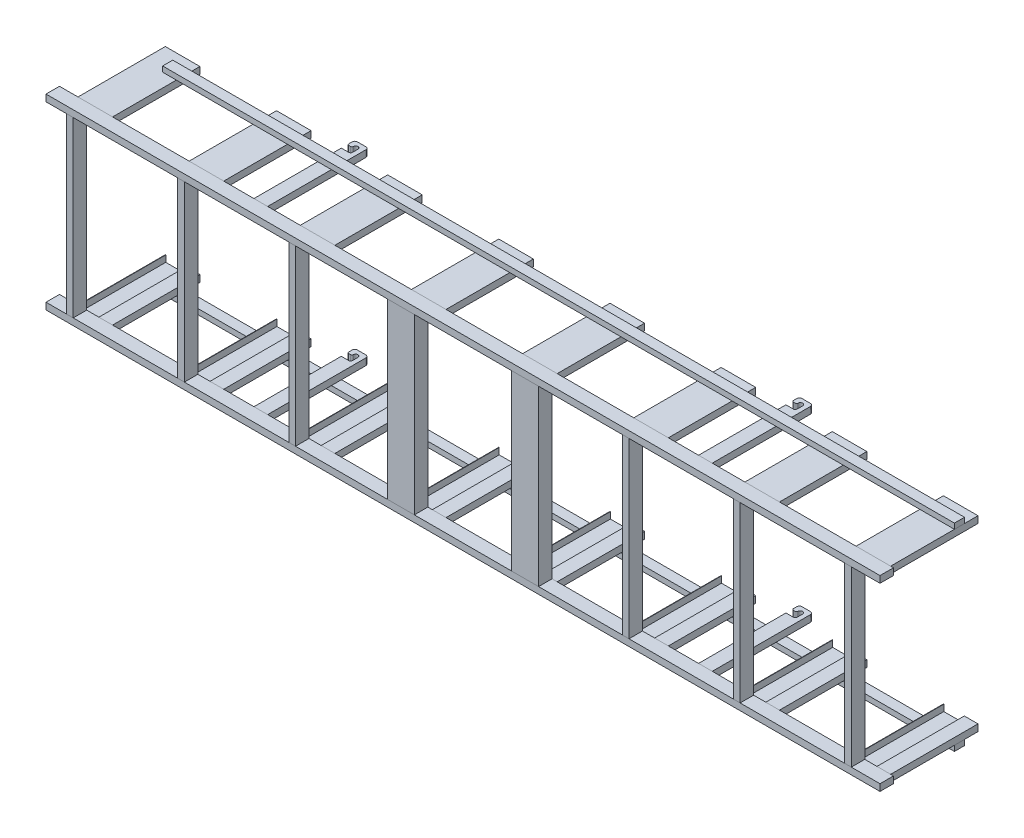
SolidWorks part; units mm, degrees
ref_plane "Front Plane" through (0, 0, 0) normal (0, 0, 1) x (1, 0, 0)
ref_plane "Top Plane" through (0, 0, 0) normal (0, 1, 0) x (1, 0, 0)
ref_plane "Right Plane" through (0, 0, 0) normal (1, 0, 0) x (0, 0, -1)
sketch "Sketch1" plane through (0, 0, 0) normal (0, 0, 1) x (1, 0, 0)
  line L0 (0, 1388) -> (6190, 1388)
  line L1 (0, 50) -> (6190, 50)
  line L2 (0, 50) -> (0, 0)
  line L3 (0, 0) -> (6190, 0)
  line L4 (6190, 50) -> (6190, 0)
  line L5 (0, 1388) -> (0, 1338)
  line L6 (0, 1338) -> (6190, 1338)
  line L7 (6190, 1388) -> (6190, 1338)
  dimension "D1" = 1288
  dimension "D2" = 50
extrude "Boss-Extrude1" add sketch "Sketch1" along normal blind 100
sketch "Sketch2" plane through (0, 0, 0) normal (0, -1, 0) x (1, 0, 0)
  line L0 (0, 100) -> (6190, 100) construction
  line L1 (2534, 100) -> (2734, 100)
  line L2 (2534, 100) -> (2534, 0)
  line L3 (2534, 0) -> (2734, 0)
  line L4 (2734, 100) -> (2734, 0)
  line L5 (0, 0) -> (6190, 0) construction
  line L6 (0, 100) -> (0, 0) construction
  line L8 (3456, 100) -> (3656, 100)
  line L9 (3456, 100) -> (3456, 0)
  line L10 (3456, 0) -> (3656, 0)
  line L11 (3656, 100) -> (3656, 0)
  point P8 (0, 50)
  dimension "D1" = 200
  dimension "D2" = 2534
  dimension "D3" = 2534
  dimension "D4" = 200
extrude "Boss-Extrude2" add sketch "Sketch2" against normal up to surface (1388 mm away) separate body up to face at (3095, 1388, 50)
sketch "Sketch3" plane through (0, 1388, 0) normal (0, 1, 0) x (1, 0, 0)
  line L2 (0, -100) -> (0, 0) construction
  line L3 (6190, -100) -> (6190, 0) construction
  line L12 (2541, -7) -> (2727, -7)
  line L13 (2727, -7) -> (2727, -93)
  line L14 (2541, -93) -> (2727, -93)
  line L15 (2541, -7) -> (2541, -93)
  line L16 (3463, -7) -> (3649, -7)
  line L17 (3649, -7) -> (3649, -93)
  line L18 (3463, -93) -> (3649, -93)
  line L19 (3463, -7) -> (3463, -93)
  point P2 (6190, -50)
  dimension "D1" = 186
  dimension "D2" = 186
  dimension "D3" = 2541
  dimension "D4" = 2541
extrude "Cut-Extrude1" [suppressed] cut sketch "Sketch3" against normal through all
sketch "Sketch4" plane through (0, 50, 0) normal (0, 1, 0) x (1, 0, 0)
  line L0 (6190, 0) -> (0, 0) construction
  line L1 (152, 0) -> (202, 0)
  line L2 (152, 0) -> (152, -100)
  line L3 (152, -100) -> (202, -100)
  line L4 (202, 0) -> (202, -100)
  line L5 (6190, -100) -> (0, -100) construction
  line L6 (0, -100) -> (0, 0) construction
  line L7 (977, 0) -> (977, -100)
  line L8 (977, 0) -> (1027, 0)
  line L9 (1027, 0) -> (1027, -100)
  line L10 (977, -100) -> (1027, -100)
  line L11 (1802, 0) -> (1802, -100)
  line L12 (1802, 0) -> (1852, 0)
  line L13 (1852, 0) -> (1852, -100)
  line L14 (1802, -100) -> (1852, -100)
  line L15 (2627, 0) -> (2627, -100) construction
  line L16 (2627, 0) -> (2677, 0) construction
  line L17 (2677, 0) -> (2677, -100) construction
  line L18 (2627, -100) -> (2677, -100) construction
  line L19 (3452, 0) -> (3452, -100) construction
  line L20 (3452, 0) -> (3502, 0) construction
  line L21 (3502, 0) -> (3502, -100) construction
  line L22 (3452, -100) -> (3502, -100) construction
  line L23 (4277, 0) -> (4277, -100)
  line L24 (4277, 0) -> (4327, 0)
  line L25 (4327, 0) -> (4327, -100)
  line L26 (4277, -100) -> (4327, -100)
  line L27 (5102, 0) -> (5102, -100)
  line L28 (5102, 0) -> (5152, 0)
  line L29 (5152, 0) -> (5152, -100)
  line L30 (5102, -100) -> (5152, -100)
  line L31 (5927, 0) -> (5927, -100)
  line L32 (5927, 0) -> (5977, 0)
  line L33 (5977, 0) -> (5977, -100)
  line L34 (5927, -100) -> (5977, -100)
  dimension "D1" = 152
  dimension "D2" = 50
  dimension "D3" = 8
extrude "Boss-Extrude3" add sketch "Sketch4" along normal up to next separate body
sketch "Sketch5" plane through (0, 0, 0) normal (0, 0, 1) x (1, 0, 0)
  line L0 (137.4, 1388) -> (137.4, 1338)
  line L1 (140.4, 1385.8) -> (140.4, 1338)
  line L2 (292.4, 1385.8) -> (140.4, 1385.8)
  line L3 (394, 1388) -> (394, 1338)
  line L4 (137.4, 1388) -> (394, 1388)
  line L5 (394, 1338) -> (292.4, 1338)
  line L6 (140.4, 1338) -> (137.4, 1338)
  line L7 (292.4, 1385.8) -> (292.4, 1338)
  line L8 (152, 1338) -> (137.4, 1338) construction
  line L9 (0, 1338) -> (2534, 1338) construction
  line L10 (962.4, 1388) -> (962.4, 1338)
  line L11 (965.4, 1385.8) -> (965.4, 1338)
  line L12 (1117.4, 1385.8) -> (965.4, 1385.8)
  line L13 (1219, 1388) -> (1219, 1338)
  line L14 (962.4, 1388) -> (1219, 1388)
  line L15 (1219, 1338) -> (1117.4, 1338)
  line L16 (965.4, 1338) -> (962.4, 1338)
  line L17 (1117.4, 1385.8) -> (1117.4, 1338)
  line L18 (977, 1338) -> (962.4, 1338) construction
  line L19 (1787.4, 1388) -> (1787.4, 1338)
  line L20 (1790.4, 1385.8) -> (1790.4, 1338)
  line L21 (1942.4, 1385.8) -> (1790.4, 1385.8)
  line L22 (2044, 1388) -> (2044, 1338)
  line L23 (1787.4, 1388) -> (2044, 1388)
  line L24 (2044, 1338) -> (1942.4, 1338)
  line L25 (1790.4, 1338) -> (1787.4, 1338)
  line L26 (1942.4, 1385.8) -> (1942.4, 1338)
  line L27 (1802, 1338) -> (1787.4, 1338) construction
  line L28 (2612.4, 1388) -> (2612.4, 1338)
  line L29 (2615.4, 1385.8) -> (2615.4, 1338)
  line L30 (2767.4, 1385.8) -> (2615.4, 1385.8)
  line L31 (2869, 1388) -> (2869, 1338)
  line L32 (2612.4, 1388) -> (2869, 1388)
  line L33 (2869, 1338) -> (2767.4, 1338)
  line L34 (2615.4, 1338) -> (2612.4, 1338)
  line L35 (2767.4, 1385.8) -> (2767.4, 1338)
  line L36 (2627, 1338) -> (2612.4, 1338) construction
  line L37 (3437.4, 1388) -> (3437.4, 1338)
  line L38 (3440.4, 1385.8) -> (3440.4, 1338)
  line L39 (3592.4, 1385.8) -> (3440.4, 1385.8)
  line L40 (3694, 1388) -> (3694, 1338)
  line L41 (3437.4, 1388) -> (3694, 1388)
  line L42 (3694, 1338) -> (3592.4, 1338)
  line L43 (3440.4, 1338) -> (3437.4, 1338)
  line L44 (3592.4, 1385.8) -> (3592.4, 1338)
  line L45 (3452, 1338) -> (3437.4, 1338) construction
  line L46 (4262.4, 1388) -> (4262.4, 1338)
  line L47 (4265.4, 1385.8) -> (4265.4, 1338)
  line L48 (4417.4, 1385.8) -> (4265.4, 1385.8)
  line L49 (4519, 1388) -> (4519, 1338)
  line L50 (4262.4, 1388) -> (4519, 1388)
  line L51 (4519, 1338) -> (4417.4, 1338)
  line L52 (4265.4, 1338) -> (4262.4, 1338)
  line L53 (4417.4, 1385.8) -> (4417.4, 1338)
  line L54 (4277, 1338) -> (4262.4, 1338) construction
  line L55 (5087.4, 1388) -> (5087.4, 1338)
  line L56 (5090.4, 1385.8) -> (5090.4, 1338)
  line L57 (5242.4, 1385.8) -> (5090.4, 1385.8)
  line L58 (5344, 1388) -> (5344, 1338)
  line L59 (5087.4, 1388) -> (5344, 1388)
  line L60 (5344, 1338) -> (5242.4, 1338)
  line L61 (5090.4, 1338) -> (5087.4, 1338)
  line L62 (5242.4, 1385.8) -> (5242.4, 1338)
  line L63 (5102, 1338) -> (5087.4, 1338) construction
  line L64 (5912.4, 1388) -> (5912.4, 1338)
  line L65 (5915.4, 1385.8) -> (5915.4, 1338)
  line L66 (6067.4, 1385.8) -> (5915.4, 1385.8)
  line L67 (6169, 1388) -> (6169, 1338)
  line L68 (5912.4, 1388) -> (6169, 1388)
  line L69 (6169, 1338) -> (6067.4, 1338)
  line L70 (5915.4, 1338) -> (5912.4, 1338)
  line L71 (6067.4, 1385.8) -> (6067.4, 1338)
  line L72 (5927, 1338) -> (5912.4, 1338) construction
  line L73 (152, 694) -> (5977, 694) construction
  line L74 (152, 1338) -> (152, 50) construction
  line L75 (5977, 1338) -> (5977, 50) construction
  line L76 (5927, 50) -> (5912.4, 50) construction
  line L77 (5102, 50) -> (5087.4, 50) construction
  line L78 (4277, 50) -> (4262.4, 50) construction
  line L79 (3452, 50) -> (3437.4, 50) construction
  line L80 (2627, 50) -> (2612.4, 50) construction
  line L81 (1802, 50) -> (1787.4, 50) construction
  line L82 (977, 50) -> (962.4, 50) construction
  line L83 (152, 50) -> (137.4, 50) construction
  line L84 (6067.4, 2.2) -> (6067.4, 50)
  line L85 (5915.4, 50) -> (5912.4, 50)
  line L86 (6169, 50) -> (6067.4, 50)
  line L87 (5912.4, 0) -> (6169, 0)
  line L88 (6169, 0) -> (6169, 50)
  line L89 (6067.4, 2.2) -> (5915.4, 2.2)
  line L90 (5915.4, 2.2) -> (5915.4, 50)
  line L91 (5912.4, 0) -> (5912.4, 50)
  line L92 (5242.4, 2.2) -> (5242.4, 50)
  line L93 (5090.4, 50) -> (5087.4, 50)
  line L94 (5344, 50) -> (5242.4, 50)
  line L95 (5087.4, 0) -> (5344, 0)
  line L96 (5344, 0) -> (5344, 50)
  line L97 (5242.4, 2.2) -> (5090.4, 2.2)
  line L98 (5090.4, 2.2) -> (5090.4, 50)
  line L99 (5087.4, 0) -> (5087.4, 50)
  line L100 (4417.4, 2.2) -> (4417.4, 50)
  line L101 (4265.4, 50) -> (4262.4, 50)
  line L102 (4519, 50) -> (4417.4, 50)
  line L103 (4262.4, 0) -> (4519, 0)
  line L104 (4519, 0) -> (4519, 50)
  line L105 (4417.4, 2.2) -> (4265.4, 2.2)
  line L106 (4265.4, 2.2) -> (4265.4, 50)
  line L107 (4262.4, 0) -> (4262.4, 50)
  line L108 (3592.4, 2.2) -> (3592.4, 50)
  line L109 (3440.4, 50) -> (3437.4, 50)
  line L110 (3694, 50) -> (3592.4, 50)
  line L111 (3437.4, 0) -> (3694, 0)
  line L112 (3694, 0) -> (3694, 50)
  line L113 (3592.4, 2.2) -> (3440.4, 2.2)
  line L114 (3440.4, 2.2) -> (3440.4, 50)
  line L115 (3437.4, 0) -> (3437.4, 50)
  line L116 (2767.4, 2.2) -> (2767.4, 50)
  line L117 (2615.4, 50) -> (2612.4, 50)
  line L118 (2869, 50) -> (2767.4, 50)
  line L119 (2612.4, 0) -> (2869, 0)
  line L120 (2869, 0) -> (2869, 50)
  line L121 (2767.4, 2.2) -> (2615.4, 2.2)
  line L122 (2615.4, 2.2) -> (2615.4, 50)
  line L123 (2612.4, 0) -> (2612.4, 50)
  line L124 (1942.4, 2.2) -> (1942.4, 50)
  line L125 (1790.4, 50) -> (1787.4, 50)
  line L126 (2044, 50) -> (1942.4, 50)
  line L127 (1787.4, 0) -> (2044, 0)
  line L128 (2044, 0) -> (2044, 50)
  line L129 (1942.4, 2.2) -> (1790.4, 2.2)
  line L130 (1790.4, 2.2) -> (1790.4, 50)
  line L131 (1787.4, 0) -> (1787.4, 50)
  line L132 (1117.4, 2.2) -> (1117.4, 50)
  line L133 (965.4, 50) -> (962.4, 50)
  line L134 (1219, 50) -> (1117.4, 50)
  line L135 (962.4, 0) -> (1219, 0)
  line L136 (1219, 0) -> (1219, 50)
  line L137 (1117.4, 2.2) -> (965.4, 2.2)
  line L138 (965.4, 2.2) -> (965.4, 50)
  line L139 (962.4, 0) -> (962.4, 50)
  line L140 (292.4, 2.2) -> (292.4, 50)
  line L141 (140.4, 50) -> (137.4, 50)
  line L142 (394, 50) -> (292.4, 50)
  line L143 (137.4, 0) -> (394, 0)
  line L144 (394, 0) -> (394, 50)
  line L145 (292.4, 2.2) -> (140.4, 2.2)
  line L146 (140.4, 2.2) -> (140.4, 50)
  line L147 (137.4, 0) -> (137.4, 50)
  dimension "D1" = 50
  dimension "D2" = 50
  dimension "D3" = 8
extrude "Boss-Extrude4" add sketch "Sketch5" against normal blind 648.4 separate body
sketch "Sketch8" plane through (0, 50, 0) normal (0, 1, 0) x (1, 0, 0)
  line L0 (1443.4, 648.4) -> (1497.5, 648.4)
  line L1 (1453.4, 693.4) -> (1467.5, 693.4)
  line L2 (1443.4, 728.4) -> (1443.4, 703.4)
  line L3 (1512.5, 703.4) -> (1512.5, 663.4)
  line L4 (1545, 0) -> (1443.4, 0)
  line L5 (1443.4, 0) -> (1443.4, 648.4)
  line L6 (1545, 0) -> (1545, 728.4)
  line L7 (1463.4, 748.4) -> (1525, 748.4)
  line L8 (0, 0) -> (1443.4, 0) construction
  line L9 (6190, 0) -> (4845, 0) construction
  line L10 (4845, 0) -> (4743.4, 0)
  line L11 (4812.5, 703.4) -> (4812.5, 663.4)
  line L12 (4743.4, 728.4) -> (4743.4, 703.4)
  line L13 (4753.4, 693.4) -> (4767.5, 693.4)
  line L14 (4743.4, 0) -> (4743.4, 648.4)
  line L15 (4845, 0) -> (4845, 728.4)
  line L16 (4743.4, 648.4) -> (4797.5, 648.4)
  line L17 (4763.4, 748.4) -> (4825, 748.4)
  arc A0 (1497.5, 648.4) -> (1512.5, 663.4) centre (1497.5, 663.4) ccw
  arc A1 (1443.4, 703.4) -> (1453.4, 693.4) centre (1453.4, 703.4) ccw
  arc A2 (1463.4, 748.4) -> (1443.4, 728.4) centre (1463.4, 728.4) ccw
  arc A3 (1545, 728.4) -> (1525, 748.4) centre (1525, 728.4) ccw
  arc A4 (1512.5, 703.4) -> (1477.5, 703.4) centre (1495, 703.4) ccw
  arc A5 (1467.5, 693.4) -> (1477.5, 703.4) centre (1467.5, 703.4) ccw
  arc A6 (4845, 728.4) -> (4825, 748.4) centre (4825, 728.4) ccw
  arc A7 (4763.4, 748.4) -> (4743.4, 728.4) centre (4763.4, 728.4) ccw
  arc A8 (4767.5, 693.4) -> (4777.5, 703.4) centre (4767.5, 703.4) ccw
  arc A9 (4743.4, 703.4) -> (4753.4, 693.4) centre (4753.4, 703.4) ccw
  arc A10 (4812.5, 703.4) -> (4777.5, 703.4) centre (4795, 703.4) ccw
  arc A11 (4797.5, 648.4) -> (4812.5, 663.4) centre (4797.5, 663.4) ccw
extrude "Boss-Extrude5" add sketch "Sketch8" against normal blind 50 separate body
sketch "Sketch9" plane through (0, 1388, 0) normal (0, 1, 0) x (1, 0, 0)
  line L0 (1443.4, 648.4) -> (1497.5, 648.4)
  line L1 (1453.4, 693.4) -> (1467.5, 693.4)
  line L2 (1443.4, 728.4) -> (1443.4, 703.4)
  line L3 (1512.5, 703.4) -> (1512.5, 663.4)
  line L4 (1545, 0) -> (1443.4, 0)
  line L5 (1443.4, 0) -> (1443.4, 648.4)
  line L6 (1545, 0) -> (1545, 728.4)
  line L7 (1463.4, 748.4) -> (1525, 748.4)
  line L8 (0, 0) -> (1443.4, 0) construction
  line L9 (6190, 0) -> (4845, 0) construction
  line L10 (4845, 0) -> (4743.4, 0)
  line L11 (4812.5, 703.4) -> (4812.5, 663.4)
  line L12 (4743.4, 728.4) -> (4743.4, 703.4)
  line L13 (4753.4, 693.4) -> (4767.5, 693.4)
  line L14 (4743.4, 0) -> (4743.4, 648.4)
  line L15 (4845, 0) -> (4845, 728.4)
  line L16 (4743.4, 648.4) -> (4797.5, 648.4)
  line L17 (4763.4, 748.4) -> (4825, 748.4)
  arc A0 (1497.5, 648.4) -> (1512.5, 663.4) centre (1497.5, 663.4) ccw
  arc A1 (1443.4, 703.4) -> (1453.4, 693.4) centre (1453.4, 703.4) ccw
  arc A2 (1463.4, 748.4) -> (1443.4, 728.4) centre (1463.4, 728.4) ccw
  arc A3 (1545, 728.4) -> (1525, 748.4) centre (1525, 728.4) ccw
  arc A4 (1512.5, 703.4) -> (1477.5, 703.4) centre (1495, 703.4) ccw
  arc A5 (1467.5, 693.4) -> (1477.5, 703.4) centre (1467.5, 703.4) ccw
  arc A6 (4845, 728.4) -> (4825, 748.4) centre (4825, 728.4) ccw
  arc A7 (4763.4, 748.4) -> (4743.4, 728.4) centre (4763.4, 728.4) ccw
  arc A8 (4767.5, 693.4) -> (4777.5, 703.4) centre (4767.5, 703.4) ccw
  arc A9 (4743.4, 703.4) -> (4753.4, 693.4) centre (4753.4, 703.4) ccw
  arc A10 (4812.5, 703.4) -> (4777.5, 703.4) centre (4795, 703.4) ccw
  arc A11 (4797.5, 648.4) -> (4812.5, 663.4) centre (4797.5, 663.4) ccw
extrude "Boss-Extrude6" add sketch "Sketch9" against normal blind 50 separate body
sketch "Sketch10" plane through (6169, 0, 0) normal (1, 0, 0) x (0, 0, -1)
  line L0 (648.4, 0) -> (0, 0) construction
  line L1 (548.4, 0) -> (473.4, 0)
  line L2 (548.4, 0) -> (548.4, -40)
  line L3 (548.4, -40) -> (473.4, -40)
  line L4 (473.4, 0) -> (473.4, -40)
  line L5 (648.4, 1388) -> (0, 1388) construction
  line L6 (548.4, 1388) -> (473.4, 1388)
  line L7 (548.4, 1388) -> (548.4, 1428)
  line L8 (548.4, 1428) -> (473.4, 1428)
  line L9 (473.4, 1388) -> (473.4, 1428)
  dimension "D1" = 100
  dimension "D2" = 75
  dimension "D3" = 75
  dimension "D4" = 100
extrude "Boss-Extrude7" add sketch "Sketch10" against normal up to surface (5876.6 mm away) separate body up to face at (292.4, 1361.9, -324.2)
